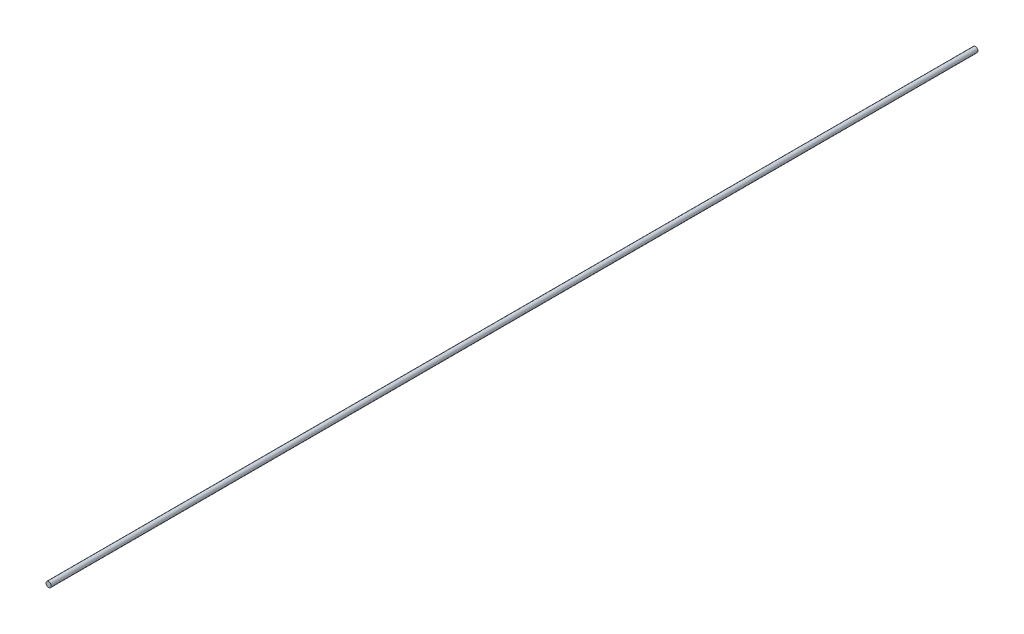
SolidWorks part; units mm, degrees
material "1060 Alloy"
ref_plane "Front Plane" through (0, 0, 0) normal (0, 0, 1) x (1, 0, 0)
ref_plane "Top Plane" through (0, 0, 0) normal (0, 1, 0) x (1, 0, 0)
ref_plane "Right Plane" through (0, 0, 0) normal (1, 0, 0) x (0, 0, -1)
sketch "Sketch1" plane through (0, 0, 0) normal (0, 0, 1) x (1, 0, 0)
  circle A0 centre (0, 0) radius 12.7
  dimension "D1" = 25.4
extrude "Boss-Extrude1" add sketch "Sketch1" along normal blind 4488.5505
equation "\"Diameter\"= 1in"
equation "\"Deflection\"= 0.009in"
equation "\"D1@Sketch1\"=\"Diameter\""
equation "\"E\"= 10000000"
equation "\"F\"= 400"
equation "\"A\"= Pi / 4 * \"Diameter\" ^ 2"
equation "\"L\"= ( \"Deflection\" * \"E\" * \"A\" / \"F\" )'inches"
equation "\"D1@Boss-Extrude1\"=\"L\""
